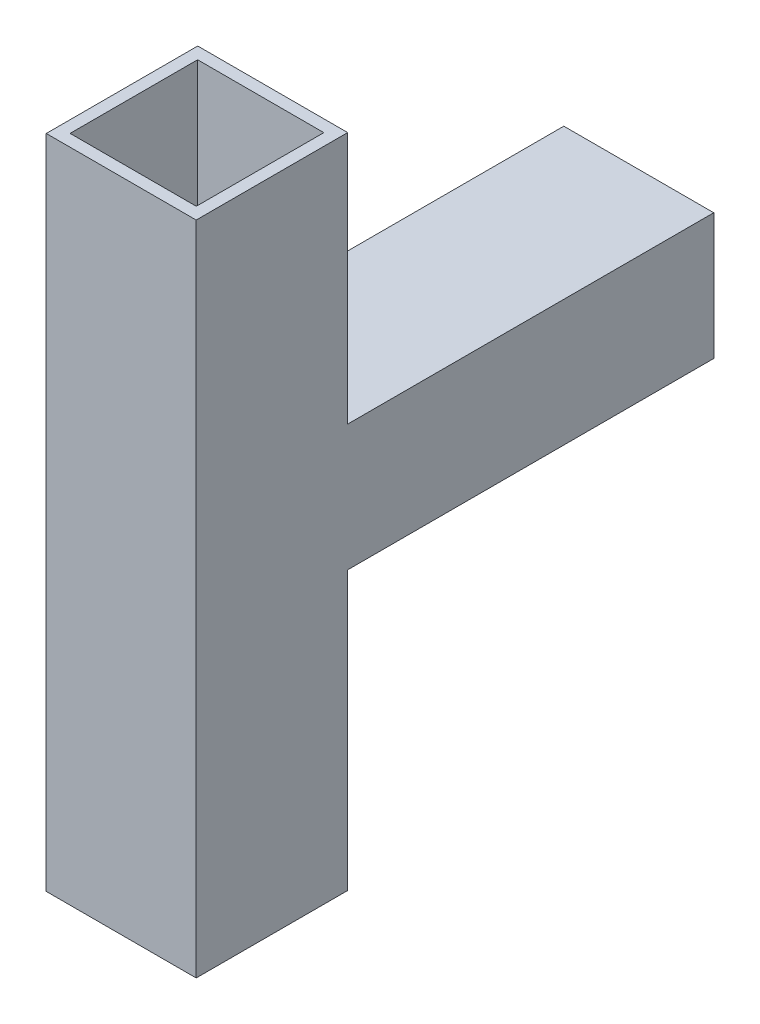
SolidWorks part; units mm, degrees
ref_plane "Front Plane" through (0, 0, 0) normal (0, 0, 1) x (1, 0, 0)
ref_plane "Top Plane" through (0, 0, 0) normal (0, 1, 0) x (1, 0, 0)
ref_plane "Right Plane" through (0, 0, 0) normal (1, 0, 0) x (0, 0, -1)
sketch "Sketch1" plane through (0, 0, 0) normal (0, 1, 0) x (1, 0, 0)
  line L1 (-2.9694, -3) -> (2.9694, -3)
  line L2 (-2.9694, -3) -> (-2.9694, 3)
  line L3 (-2.9694, 3) -> (2.9694, 3)
  line L4 (2.9694, -3) -> (2.9694, 3)
  line L5 (-2.9694, -3) -> (2.9694, 3) construction
  line L6 (-2.9694, 3) -> (2.9694, -3) construction
  line L7 (-2.5, -2.5258) -> (2.5, -2.5258)
  line L8 (-2.5, -2.5258) -> (-2.5, 2.5258)
  line L9 (-2.5, 2.5258) -> (2.5, 2.5258)
  line L10 (2.5, -2.5258) -> (2.5, 2.5258)
  line L11 (-2.5, -2.5258) -> (2.5, 2.5258) construction
  line L12 (-2.5, 2.5258) -> (2.5, -2.5258) construction
  point P0 (0, 0)
  point P6 (0, 0)
  dimension "D1" = 6
  dimension "D2" = 5
extrude "Boss-Extrude1" add sketch "Sketch1" along normal blind 26
sketch "Sketch4" plane through (0, 0, -3) normal (0, 0, -1) x (-1, 0, 0)
  line L0 (-2.9694, 26) -> (-2.9694, 0) construction
  line L1 (-2.9694, 11) -> (2.9694, 11)
  line L2 (-2.9694, 11) -> (-2.9694, 16)
  line L3 (-2.9694, 16) -> (2.9694, 16)
  line L4 (2.9694, 11) -> (2.9694, 16)
  line L5 (2.9694, 26) -> (2.9694, 0) construction
  line L6 (-2.9694, 26) -> (2.9694, 26) construction
  dimension "D1" = 5
  dimension "D2" = 10
extrude "Boss-Extrude2" add sketch "Sketch4" along normal blind 14.5
sketch "Sketch5" plane through (0, 0, -17.5) normal (0, 0, -1) x (-1, 0, 0)
  line L0 (-2.9694, 11) -> (2.9694, 11) construction
  line L1 (-1.9694, 11.5) -> (2.0306, 11.5)
  line L2 (-1.9694, 11.5) -> (-1.9694, 15.5)
  line L3 (-1.9694, 15.5) -> (2.0306, 15.5)
  line L4 (2.0306, 11.5) -> (2.0306, 15.5)
  line L5 (-1.9694, 11.5) -> (2.0306, 15.5) construction
  line L6 (-1.9694, 15.5) -> (2.0306, 11.5) construction
  line L7 (-2.9694, 16) -> (-2.9694, 11) construction
  point P0 (0.0306, 13.5)
  dimension "D1" = 4
  dimension "D2" = 4
  dimension "D3" = 0.5
  dimension "D4" = 1
extrude "Cut-Extrude1" cut sketch "Sketch5" against normal up to surface (14.9742 mm away) up to face at (0, 13, -2.5258)
